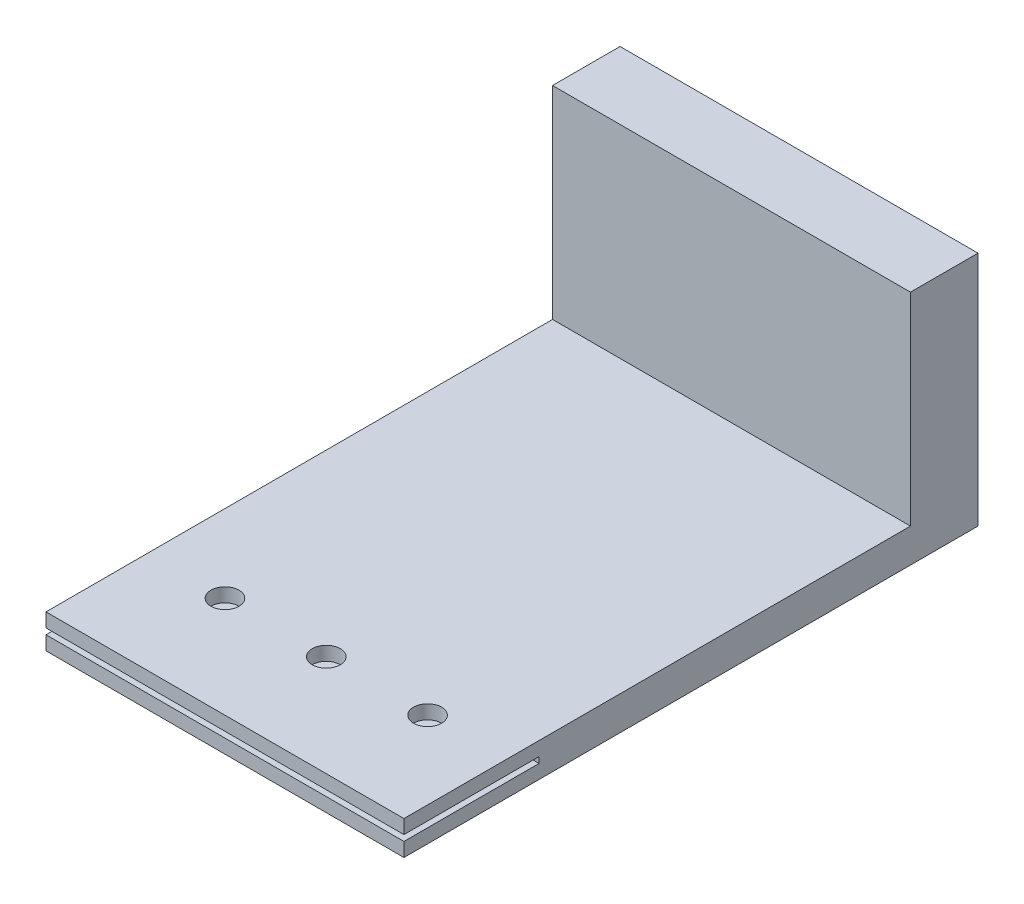
SolidWorks part; units mm, degrees
ref_plane "Front Plane" through (0, 0, 0) normal (0, 0, 1) x (1, 0, 0)
ref_plane "Top Plane" through (0, 0, 0) normal (0, 1, 0) x (1, 0, 0)
ref_plane "Right Plane" through (0, 0, 0) normal (1, 0, 0) x (0, 0, -1)
sketch "Sketch4" plane through (0, 0, 0) normal (0, 1, 0) x (1, 0, 0)
  line L1 (-53, -85) -> (53, -85)
  line L2 (-53, -85) -> (-53, 85)
  line L3 (-53, 85) -> (53, 85)
  line L4 (53, -85) -> (53, 85)
  line L5 (-53, -85) -> (53, 85) construction
  line L6 (-53, 85) -> (53, -85) construction
  point P0 (0, 0)
  dimension "D1" = 106
  dimension "D2" = 170
extrude "Boss-Extrude4" add sketch "Sketch4" along normal blind 10
sketch "Sketch5" plane through (0, 10, 0) normal (0, 1, 0) x (1, 0, 0)
  line L0 (53, -85) -> (53, 85) construction
  line L1 (-53, 85) -> (53, 85)
  line L2 (-53, 85) -> (-53, 65)
  line L3 (-53, 65) -> (53, 65)
  line L4 (53, 85) -> (53, 65)
  line L5 (0, 0) -> (53, 0) construction
  line L6 (-53, -65) -> (53, -65)
  line L7 (53, -85) -> (53, -65)
  line L8 (-53, -85) -> (53, -85)
  line L9 (-53, -85) -> (-53, -65)
  dimension "D1" = 20
extrude "Boss-Extrude5" add sketch "Sketch5" along normal blind 60
sketch "Sketch6" plane through (0, 0, 85) normal (0, 0, 1) x (1, 0, 0)
  line L0 (53, 70) -> (53, 0) construction
  line L1 (-53, 0) -> (53, 0)
  line L2 (-53, 0) -> (-53, 10)
  line L3 (-53, 10) -> (53, 10)
  line L4 (53, 0) -> (53, 10)
  line L5 (0, 0) -> (0, 10) construction
  line L7 (-53, 4.125) -> (53, 4.125)
  line L8 (-53, 4.125) -> (-53, 5.875)
  line L9 (-53, 5.875) -> (53, 5.875)
  line L10 (53, 4.125) -> (53, 5.875)
  line L11 (-53, 4.125) -> (53, 5.875) construction
  line L12 (-53, 5.875) -> (53, 4.125) construction
  point P9 (0, 5)
  dimension "D1" = 10
  dimension "D2" = 1.75
extrude "Cut-Extrude2" cut sketch "Sketch6" against normal blind 40 contours L9 L2 L7 L4
sketch "Sketch7" plane through (0, 10, 0) normal (0, 1, 0) x (1, 0, 0)
  line L0 (53, -65) -> (53, 65) construction
  line L1 (-53, -65) -> (53, -65)
  line L2 (-53, -65) -> (-53, -45)
  line L3 (-53, -45) -> (53, -45)
  line L4 (53, -65) -> (53, -45)
  line L5 (-53, -55) -> (53, -55) construction
  circle A0 centre (0, -55) radius 4.15
  circle A1 centre (30, -55) radius 4.15
  circle A2 centre (-30, -55) radius 4.15
  dimension "D2" = 8.3
  dimension "D1" = 20
  dimension "D3" = 2
  dimension "D4" = 2
extrude "Cut-Extrude3" cut sketch "Sketch7" against normal blind 40 contours A2 | A0 | A1
sketch "Sketch8" plane through (0, 0, 65) normal (0, 0, -1) x (-1, 0, 0)
  line L1 (-53, 70) -> (53, 70)
  line L2 (-53, 70) -> (-53, 10)
  line L3 (-53, 10) -> (53, 10)
  line L4 (53, 70) -> (53, 10)
extrude "Cut-Extrude4" cut sketch "Sketch8" against normal blind 40
